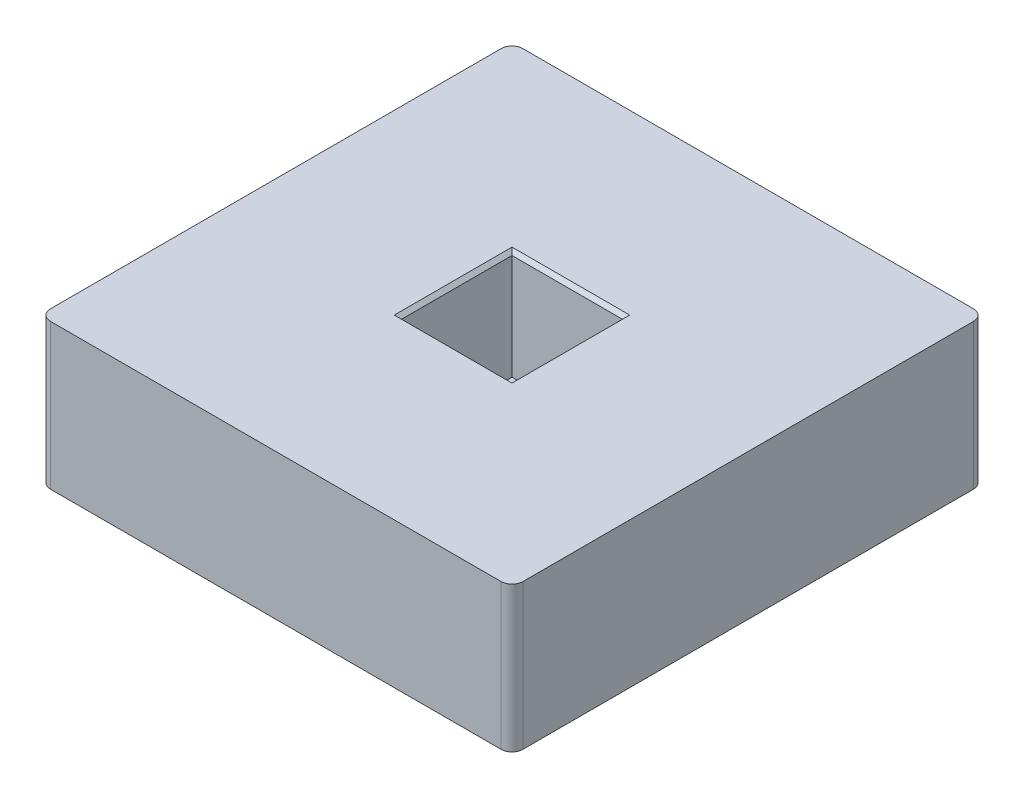
SolidWorks part; units mm, degrees
ref_plane "Front Plane" through (0, 0, 0) normal (0, 0, 1) x (1, 0, 0)
ref_plane "Top Plane" through (0, 0, 0) normal (0, 1, 0) x (1, 0, 0)
ref_plane "Right Plane" through (0, 0, 0) normal (1, 0, 0) x (0, 0, -1)
sketch "Sketch1" plane through (0, 0, 0) normal (0, 1, 0) x (1, 0, 0)
  line L1 (-65, 65) -> (65, 65)
  line L2 (-65, 65) -> (-65, -65)
  line L3 (-65, -65) -> (65, -65)
  line L4 (65, 65) -> (65, -65)
  line L5 (-65, 65) -> (65, -65) construction
  line L6 (-65, -65) -> (65, 65) construction
  point P0 (0, 0)
  dimension "D1" = 130
  dimension "D2" = 130
extrude "Boss-Extrude1" add sketch "Sketch1" along normal blind 40
fillet "Fillet1" radius 3 4 edges at (65, 20, -65) (-65, 20, -65) (-65, 20, 65) (65, 20, 65)
sketch "Sketch2" plane through (0, 40, 0) normal (0, 1, 0) x (1, 0, 0)
  line L1 (-15.2, 15.2) -> (15.2, 15.2)
  line L2 (-15.2, 15.2) -> (-15.2, -15.2)
  line L3 (-15.2, -15.2) -> (15.2, -15.2)
  line L4 (15.2, 15.2) -> (15.2, -15.2)
  line L5 (-15.2, 15.2) -> (15.2, -15.2) construction
  line L6 (-15.2, -15.2) -> (15.2, 15.2) construction
  point P0 (0, 0)
  dimension "D1" = 30.4
  dimension "D2" = 30.4
extrude "Cut-Extrude1" cut sketch "Sketch2" against normal blind 30
chamfer "Chamfer1" distance 1 angle 45 4 edges at (0, 40, -15.2) (-15.2, 40, 0) (0, 40, 15.2) (15.2, 40, 0)
equation "\"board_w\"= 33.8"
equation "\"board_l\"= 41"
equation "\"stack_h\"= 19.5"
equation "\"module_w\"= 9.9"
equation "\"lens_d\"= 7.8"
equation "\"lens_from_end\"= 8"
equation "\"usb_w\"= 13"
equation "\"plug_h\"= 7"
equation "\"usb_from_back\"= 6"
equation "\"clear\"= 0.4"
equation "\"wall\"= 3"
equation "\"floor_t\"= 2.5"
equation "\"pocket_clear\"= 0.3"
equation "\"lens_clear\"= 0.6"
equation "\"plate_w\"= 16"
equation "\"plate_clear\"= 0.3"
equation "\"plate_t\"= 1.2"
equation "\"plate_seat\"= 0.8"
equation "\"window_d\"= 12"
equation "\"lid_t\"= 2"
equation "\"lid_gap\"= 1"
equation "\"groove_d\"= 1.2"
equation "\"groove_clear\"= 0.15"
equation "\"lip_top\"= 1.2"
equation "\"side_clear\"= 0.2"
equation "\"slide_clear\"= 0.2"
equation "\"ball_d\"= 16"
equation "\"ball_clear\"= 0.3"
equation "\"lip\"= 1.2"
equation "\"cup_floor\"= 1.2"
equation "\"cup_d\"= 26"
equation "\"slit_w\"= 1.5"
equation "\"slit_depth\"= 9"
equation "\"lug_w\"= 16"
equation "\"m3_hole\"= 3.4"
equation "\"m3_nut\"= 5.7"
equation "\"m3_nut_d\"= 2.6"
equation "\"boss_d\"= 20"
equation "\"boss_h\"= 8"
equation "\"nut_af\"= 11.4"
equation "\"nut_t\"= 5.8"
equation "\"screw_hole\"= 6.6"
equation "\"post_w\"= 30"
equation "\"post_len\"= 120"
equation "\"spigot_w\"= 23.7"
equation "\"bore_w\"= 24"
equation "\"spigot_len\"= 25"
equation "\"base_w\"= 130"
equation "\"base_h\"= 40"
equation "\"hole_depth\"= 30"
equation "\"base_clear\"= 0.4"
equation "\"base_col\"= 42"
equation "\"base_shell\"= 3"
equation "\"head_h\"= 50"
equation "\"arm_under\"= 30"
equation "\"arm_reach\"= 45"
equation "\"face_run\"= 20"
equation "\"bb_d\"= 24"
equation "\"bb_h\"= 10"
equation "\"neck_d\"= 8"
equation "\"ball_drop\"= 14"
equation "\"in_l\"= \"board_l\" + 2 * \"clear\""
equation "\"in_w\"= \"board_w\" + 2 * \"clear\""
equation "\"out_l\"= \"in_l\" + 2 * \"wall\""
equation "\"out_w\"= \"in_w\" + 2 * \"wall\""
equation "\"y_groove\"= \"floor_t\" - \"plate_seat\" + \"stack_h\" + \"lid_gap\""
equation "\"groove_h\"= \"lid_t\" + 2 * \"groove_clear\""
equation "\"tray_h\"= \"y_groove\" + \"groove_h\" + \"lip_top\""
equation "\"lid_w\"= \"in_w\" + 2 * \"groove_d\" - 2 * \"side_clear\""
equation "\"lid_right\"= \"in_l\" / 2 + \"groove_d\" - \"slide_clear\""
equation "\"lid_left\"= \"out_l\" / 2"
equation "\"open_d\"= \"ball_d\" - 2 * \"lip\""
equation "\"c_ball\"= sqr( ( ( \"ball_d\" + \"ball_clear\" ) / 2 ) ^ 2 - ( \"open_d\" / 2 ) ^ 2 )"
equation "\"cup_h\"= \"cup_floor\" + ( \"ball_d\" + \"ball_clear\" ) / 2 + \"c_ball\""
equation "\"lug_in\"= \"cup_d\" / 2 - 5"
equation "\"lug_out\"= \"cup_d\" / 2 + 4"
equation "\"D1@Sketch1\"=\"base_w\""
equation "\"D1@Boss-Extrude1\"=\"base_h\""
equation "\"D1@Fillet1\"=3"
equation "\"D2@Sketch2\"=\"post_w\"+ \"base_clear\""
equation "\"D1@Cut-Extrude1\"=\"hole_depth\""
